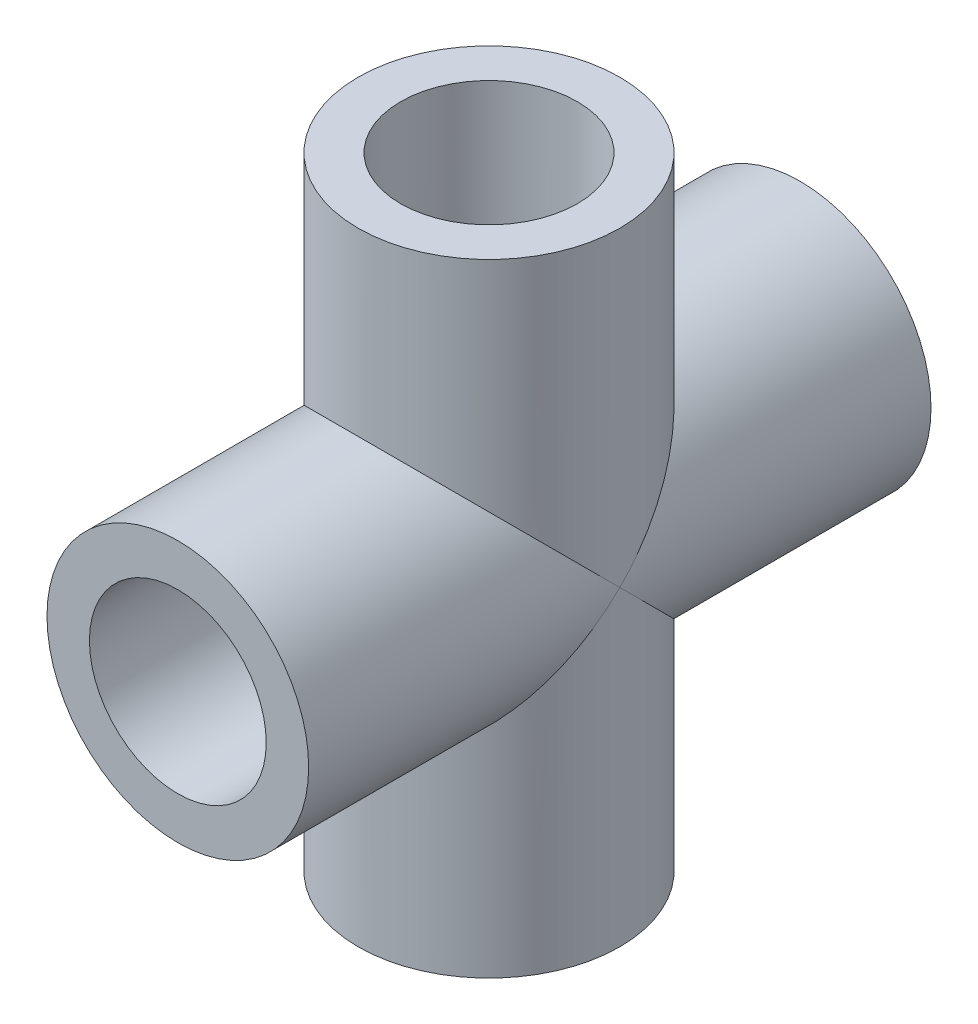
SolidWorks part; units mm, degrees
ref_plane "Front Plane" through (0, 0, 0) normal (0, 0, 1) x (1, 0, 0)
ref_plane "Top Plane" through (0, 0, 0) normal (0, 1, 0) x (1, 0, 0)
ref_plane "Right Plane" through (0, 0, 0) normal (1, 0, 0) x (0, 0, -1)
sketch "Sketch1" plane through (0, 0, 0) normal (0, 0, 1) x (1, 0, 0)
  circle A0 centre (0, 0) radius 6.25
  dimension "D1" = 12.5
extrude "Extrude-Thin3" add sketch "Sketch1" along normal blind 44 thin contours A0
sketch "Sketch3" plane through (0, 0, 0) normal (0, 1, 0) x (1, 0, 0)
  line L0 (-9.25, -22) -> (9.25, -22) construction
  line L1 (-9.25, 0) -> (-9.25, -44) construction
  line L2 (9.25, -44) -> (9.25, 0) construction
  line L3 (0, 0) -> (0, -44) construction
  line L4 (-9.25, -44) -> (9.25, -44) construction
  circle A0 centre (0, -22) radius 6.25
  dimension "D1" = 12.5
extrude "Extrude-Thin4" add sketch "Sketch3" along normal mid plane 44 thin
